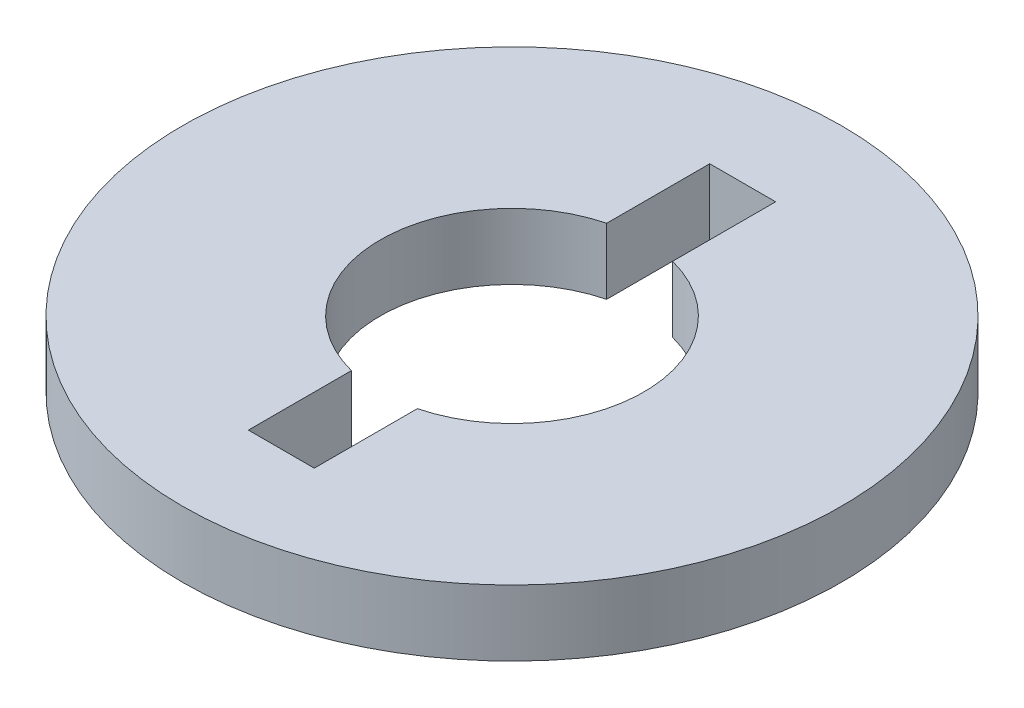
SolidWorks part; units mm, degrees
ref_plane "Front Plane" through (0, 0, 0) normal (0, 0, 1) x (1, 0, 0)
ref_plane "Top Plane" through (0, 0, 0) normal (0, 1, 0) x (1, 0, 0)
ref_plane "Right Plane" through (0, 0, 0) normal (1, 0, 0) x (0, 0, -1)
sketch "Sketch1" plane through (0, 0, 0) normal (0, 1, 0) x (1, 0, 0)
  line L0 (0.5, 1.9365) -> (0.5, 3.5)
  line L1 (-0.5, -3.5) -> (0.5, -3.5)
  line L2 (-0.5, -3.5) -> (-0.5, -1.9365)
  line L3 (-0.5, 3.5) -> (0.5, 3.5)
  line L4 (0.5, -3.5) -> (0.5, -1.9365)
  line L5 (-0.5, -3.5) -> (0.5, 3.5) construction
  line L6 (-0.5, 3.5) -> (0.5, -3.5) construction
  line L7 (-0.5, 1.9365) -> (-0.5, 3.5)
  circle A0 centre (0, 0) radius 5
  arc A1 (-0.5, 1.9365) -> (-0.5, -1.9365) centre (0, 0) ccw
  arc A2 (0.5, -1.9365) -> (0.5, 1.9365) centre (0, 0) ccw
  dimension "D1" = 10
  dimension "D2" = 4
  dimension "D3" = 1
  dimension "D4" = 7
extrude "Boss-Extrude1" add sketch "Sketch1" along normal blind 1
